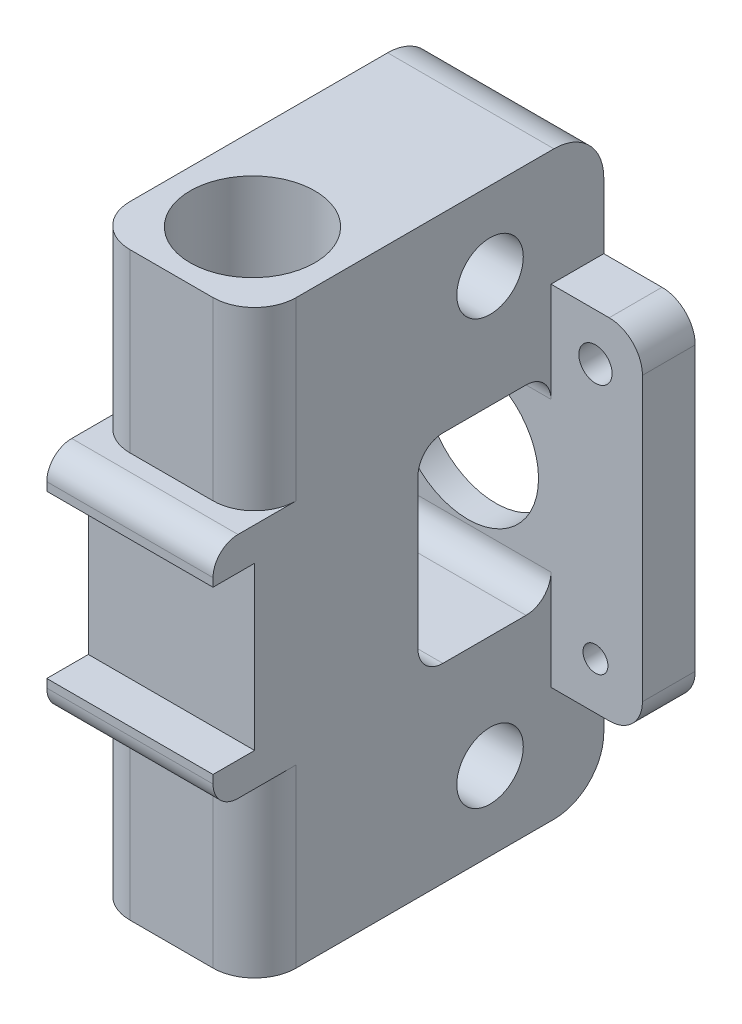
SolidWorks part; units mm, degrees
material "ABS"
ref_plane "Front Plane" through (0, 0, 0) normal (0, 0, 1) x (1, 0, 0)
ref_plane "Top Plane" through (0, 0, 0) normal (0, 1, 0) x (1, 0, 0)
ref_plane "Right Plane" through (0, 0, 0) normal (1, 0, 0) x (0, 0, -1)
sketch "Sketch1" plane through (0, 0, 0) normal (0, 1, 0) x (1, 0, 0)
  line L1 (-10, -21) -> (10, -21)
  line L2 (-10, -21) -> (-10, 21)
  line L3 (-10, 21) -> (10, 21)
  line L4 (10, -21) -> (10, 21)
  line L5 (-10, -21) -> (10, 21) construction
  line L6 (-10, 21) -> (10, -21) construction
  point P0 (0, 0)
  dimension "D1" = 20
  dimension "D2" = 42
extrude "Boss-Extrude1" add sketch "Sketch1" along normal blind 69.85
fillet "Fillet1" radius 5 2 edges at (10, 34.925, 21) (-10, 34.925, 21)
sketch "Sketch3" plane through (0, 0, -21) normal (0, 0, -1) x (-1, 0, 0)
  line L0 (-10, 69.85) -> (10, 0) construction
  line L1 (10, 0) -> (-10, 0) construction
  line L2 (-10, 0) -> (10, 69.85) construction
  line L4 (-21, 13.925) -> (21, 13.925)
  line L5 (-21, 13.925) -> (-21, 55.925)
  line L6 (-21, 55.925) -> (21, 55.925)
  line L7 (21, 13.925) -> (21, 55.925)
  line L8 (-21, 13.925) -> (21, 55.925) construction
  line L9 (-21, 55.925) -> (21, 13.925) construction
  point P4 (0, 34.925)
  dimension "D1" = 42
  dimension "D2" = 42
extrude "Boss-Extrude2" add sketch "Sketch3" against normal blind 6.35
sketch "Sketch4" plane through (10, 0, 0) normal (1, 0, 0) x (0, 0, -1)
  line L1 (14.65, 34.925) -> (-16, 34.925) construction
  line L2 (14.65, 13.925) -> (14.65, 55.925) construction
  line L3 (-16, 69.85) -> (-16, 0) construction
  line L5 (14.65, 22.925) -> (-1.35, 22.925)
  line L6 (14.65, 22.925) -> (14.65, 46.925)
  line L8 (14.65, 46.925) -> (-1.35, 46.925)
  line L9 (-1.35, 22.925) -> (-1.35, 46.925)
  line L10 (14.65, 22.925) -> (-1.35, 46.925) construction
  line L11 (14.65, 46.925) -> (-1.35, 22.925) construction
  point P6 (6.65, 34.925)
  dimension "D1" = 0
  dimension "D2" = 16
  dimension "D3" = 24
extrude "Cut-Extrude2" cut sketch "Sketch4" against normal through all
sketch "Sketch5" plane through (0, 0, -21) normal (0, 0, -1) x (-1, 0, 0)
  line L0 (-21, 55.925) -> (21, 13.925) construction
  line L2 (-21, 13.925) -> (21, 55.925) construction
  circle A0 centre (0, 34.925) radius 13
  dimension "D1" = 26
extrude "Cut-Extrude3" cut sketch "Sketch5" against normal blind 3
sketch "Sketch6" plane through (0, 0, -21) normal (0, 0, -1) x (-1, 0, 0)
  line L0 (-21, 55.925) -> (21, 13.925) construction
  line L1 (21, 13.925) -> (-21, 13.925) construction
  line L2 (-21, 13.925) -> (21, 55.925) construction
sketch "Sketch7" plane through (0, 0, -18) normal (0, 0, -1) x (-1, 0, 0)
  line L1 (-11.4572, 28.7824) -> (11.4572, 41.0676) construction
  circle A0 centre (0, 34.925) radius 13 construction
  circle A1 centre (0, 34.925) radius 8.5
  dimension "D1" = 17
extrude "Cut-Extrude4" cut sketch "Sketch7" against normal up to next
sketch "Sketch8" plane through (10, 0, 0) normal (1, 0, 0) x (0, 0, -1)
  line L0 (21, 34.925) -> (-16, 34.925) construction
  line L1 (21, 13.925) -> (21, 55.925) construction
  line L2 (-16, 69.85) -> (-16, 0) construction
  circle A0 centre (7.3182, 60.425) radius 4
  circle A1 centre (7.3182, 9.425) radius 4
  dimension "D1" = 8
  dimension "D2" = 25.5
extrude "Cut-Extrude5" cut sketch "Sketch8" against normal through all
fillet "Fillet2" radius 6 2 edges at (0, 69.85, -21) (0, 0, -21)
fillet "Fillet3" radius 4 4 edges at (21, 13.925, -17.825) (21, 55.925, -17.825) (-21, 13.925, -17.825) (-21, 55.925, -17.825)
fillet "Fillet4" radius 3 4 edges at (0, 46.925, -14.65) (0, 22.925, -14.65) (0, 22.925, 1.35) (0, 46.925, 1.35)
sketch "Sketch9" plane through (0, 0, 21) normal (0, 0, 1) x (1, 0, 0)
  line L0 (0, 0) -> (0, 69.85) construction
  line L1 (-5, 69.85) -> (5, 69.85) construction
  line L2 (-10, 0) -> (-10, 69.85) construction
  line L3 (10, 21.175) -> (-10, 21.175)
  line L4 (10, 21.175) -> (10, 48.675)
  line L5 (10, 48.675) -> (-10, 48.675)
  line L6 (-10, 21.175) -> (-10, 48.675)
  line L7 (10, 21.175) -> (-10, 48.675) construction
  line L8 (10, 48.675) -> (-10, 21.175) construction
  point P5 (0, 34.925)
  dimension "D1" = 27.5
extrude "Boss-Extrude3" add sketch "Sketch9" against normal blind 6.35
sketch "Sketch2" plane through (0, 69.85, 0) normal (0, 1, 0) x (1, 0, 0)
  circle A0 centre (0, -11.2544) radius 7.5
  dimension "D1" = 15
extrude "Cut-Extrude1" cut sketch "Sketch2" against normal through all
sketch "Sketch10" plane through (0, 0, 21) normal (0, 0, 1) x (1, 0, 0)
  line L0 (10, 21.175) -> (10, 48.675) construction
  line L1 (-10, 21.175) -> (10, 21.175)
  line L2 (-10, 21.175) -> (-10, 25.175)
  line L3 (-10, 25.175) -> (10, 25.175)
  line L4 (10, 21.175) -> (10, 25.175)
  line L5 (-10, 34.925) -> (10, 34.925) construction
  line L6 (-10, 48.675) -> (-10, 21.175) construction
  line L7 (10, 48.675) -> (10, 44.675)
  line L8 (-10, 44.675) -> (10, 44.675)
  line L9 (-10, 48.675) -> (-10, 44.675)
  line L10 (-10, 48.675) -> (10, 48.675)
  dimension "D1" = 4
extrude "Boss-Extrude4" add sketch "Sketch10" along normal blind 5
fillet "Fillet6" radius 3 2 edges at (0, 48.675, 26) (0, 21.175, 26)
extrude "Cut-Extrude6" cut sketch "Sketch11" against normal blind 7
sketch "Sketch11" plane through (85.4308, 34.8223, -21) normal (0, 0, -1) x (-1, 0, 0)
  line L0 (85.4308, 20.6027) -> (85.4308, -20.3973) construction
  line L1 (65.6024, 19.9311) -> (105.2592, -19.7257) construction
  circle A0 centre (70.0808, 15.4527) radius 2
  circle A5 centre (100.7808, -15.2473) radius 1.5
  circle A6 centre (70.0808, -15.2473) radius 1.5
  circle A7 centre (100.7808, 15.4527) radius 2
